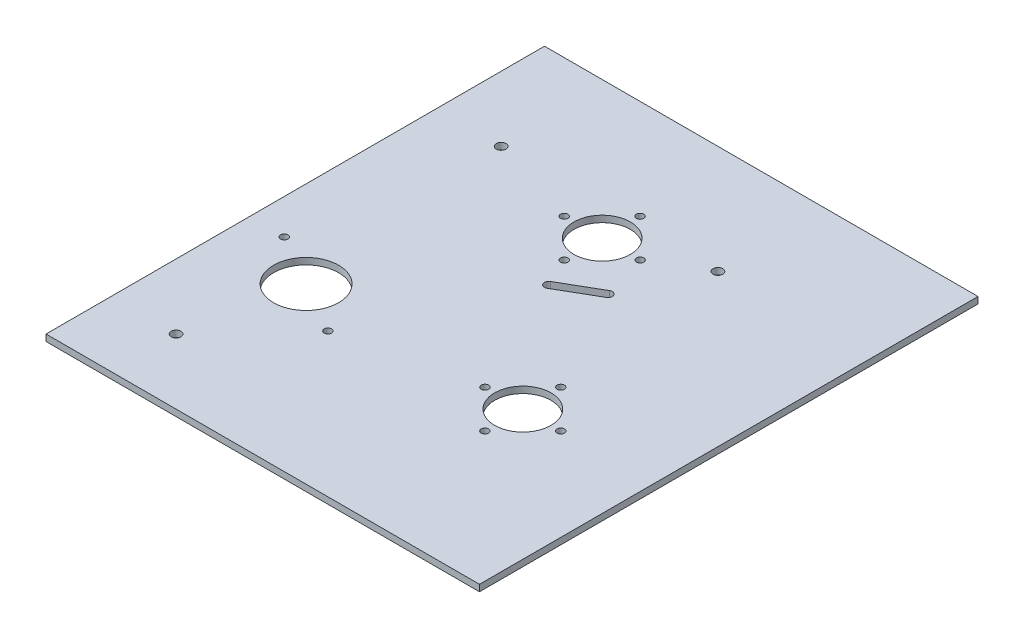
SolidWorks part; units mm, degrees
ref_plane "Front" through (0, 0, 0) normal (0, 0, 1) x (1, 0, 0)
ref_plane "Top" through (0, 0, 0) normal (0, 1, 0) x (1, 0, 0)
ref_plane "Right" through (0, 0, 0) normal (1, 0, 0) x (0, 0, -1)
sketch "Sketch1" plane through (0, 0, 0) normal (0, 1, 0) x (1, 0, 0)
  line L1 (0, 0) -> (200, 0)
  line L2 (0, 0) -> (0, 200)
  line L3 (0, 200) -> (200, 200)
  line L4 (200, 0) -> (200, 200)
  dimension "D1" = 200
  dimension "D2" = 200
extrude "Boss-Extrude1" add sketch "Sketch1" along normal blind 3
sketch "Sketch2" plane through (0, 3, 0) normal (0, 1, 0) x (1, 0, 0)
  line L0 (90, 136.6025) -> (140, 50) construction
  line L1 (0, 0) -> (200, 0) construction
  line L2 (200, 0) -> (200, 200) construction
  line L3 (140, 50) -> (40, 50) construction
  line L4 (96.3397, 105.6218) -> (113.6603, 115.6218) construction
  line L5 (95.3397, 107.3538) -> (112.6603, 117.3538)
  line L6 (97.3397, 103.8897) -> (114.6603, 113.8897)
  line L7 (13.5065, 76.4935) -> (66.4935, 23.5065) construction
  circle A0 centre (90, 136.6025) radius 13
  circle A1 centre (140, 50) radius 13
  arc A2 (95.3397, 107.3538) -> (97.3397, 103.8897) centre (96.3397, 105.6218) ccw
  arc A3 (114.6603, 113.8897) -> (112.6603, 117.3538) centre (113.6603, 115.6218) ccw
  circle A4 centre (40, 50) radius 15
  point P12 (105, 110.6218)
  dimension "D1" = 26
  dimension "D2" = 26
  dimension "D7" = 2
  dimension "D11" = 30
  dimension "D3" = 30
  dimension "D4" = 50
  dimension "D5" = 100
  dimension "D6" = 60
  dimension "D8" = 20
  dimension "D9" = 100
  dimension "D10" = 100
  dimension "D12" = 74.935
extrude "Cut-Extrude1" cut sketch "Sketch2" against normal through all
hole_wizard "M3 Clearance Hole1" positions "Sketch3" profile "Sketch4" hole size "M3" standard "ISO" end condition through all
sketch "Sketch3" plane through (0, 3, 0) normal (0, 1, 0) x (1, 0, 0)
  circle A0 centre (140, 50) radius 17.5 construction
  circle A1 centre (90, 136.6025) radius 17.5 construction
  point P0 (140, 67.5)
  point P7 (122.5, 50)
  point P9 (157.5, 50)
  point P11 (140, 32.5)
  point P20 (90, 119.1025)
  point P22 (72.5, 136.6025)
  point P24 (107.5, 136.6025)
  point P26 (90, 154.1025)
  dimension "D1" = 35
  dimension "D2" = 35
sketch "Sketch4" plane through (140, 3, -67.5) normal (1, 0, 0) x (0, 0, 1)
  line L0 (0, 0) -> (0, 3)
  line L1 (0, 3) -> (1.7, 3)
  line L2 (1.7, 3) -> (1.7, 0)
  line L5 (1.7, 0) -> (0, 0)
  line L11 (0, -6.35) -> (0, 107.95) construction
  dimension "Thru Hole Dia." = 3.4
  dimension "Thru Hole Depth" = 3
hole_wizard "M3 Clearance Hole2" positions "Sketch6" profile "Sketch7" hole size "M3" standard "ISO" end condition through all
sketch "Sketch6" plane through (0, 3, 0) normal (0, 1, 0) x (1, 0, 0)
  line L0 (16.1843, 63.75) -> (63.8157, 36.25) construction
  line L1 (40, 50) -> (90, 136.6025) construction
  circle A0 centre (40, 50) radius 15 construction
  circle A1 centre (40, 50) radius 15 construction
  point P1 (16.1843, 63.75)
  point P2 (63.8157, 36.25)
  dimension "D1" = 55
sketch "Sketch7" plane through (16.1843, 3, -63.75) normal (1, 0, 0) x (0, 0, 1)
  line L0 (0, 0) -> (0, 3)
  line L1 (0, 3) -> (1.7, 3)
  line L2 (1.7, 3) -> (1.7, 0)
  line L5 (1.7, 0) -> (0, 0)
  line L11 (0, -6.35) -> (0, 107.95) construction
  dimension "Thru Hole Dia." = 3.4
  dimension "Thru Hole Depth" = 3
sketch "Sketch8" plane through (0, 3, 0) normal (0, 1, 0) x (1, 0, 0)
  line L1 (0, 0) -> (200, 0)
  line L2 (0, 0) -> (0, -30)
  line L3 (0, -30) -> (200, -30)
  line L4 (200, 0) -> (200, -30)
  dimension "D1" = 30
extrude "Boss-Extrude2" add sketch "Sketch8" against normal up to surface (3 mm away) up to face at (16.1843, 0, -62.05)
hole_wizard "M4 Clearance Hole1" positions "Sketch9" profile "Sketch10" hole size "M4" standard "ISO"
sketch "Sketch9" plane through (0, 3, 0) normal (0, 1, 0) x (1, 0, 0)
  line L0 (30, 0) -> (30, 150) construction
  line L1 (30, 150) -> (130, 150) construction
  line L3 (0, 200) -> (0, -30) construction
  line L4 (200, 200) -> (0, 200) construction
  point P0 (30, 0)
  point P2 (30, 150)
  point P4 (130, 150)
  point P14 (0, 0)
  dimension "D1" = 30
  dimension "D2" = 50
  dimension "D3" = 100
  dimension "D4" = 200
sketch "Sketch10" plane through (30, 3, 0) normal (1, 0, 0) x (0, 0, 1)
  line L0 (0, 0) -> (0, 8.3519)
  line L1 (0, 8.3519) -> (2.25, 7)
  line L2 (2.25, 7) -> (2.25, 0)
  line L5 (2.25, 0) -> (0, 0)
  line L10 (0, 8.3519) -> (-2.25, 7) construction
  line L11 (0, -6.35) -> (0, 107.95) construction
  dimension "Hole Dia." = 4.5
  dimension "Hole Depth" = 7
  dimension "Drill Angle" = 118
